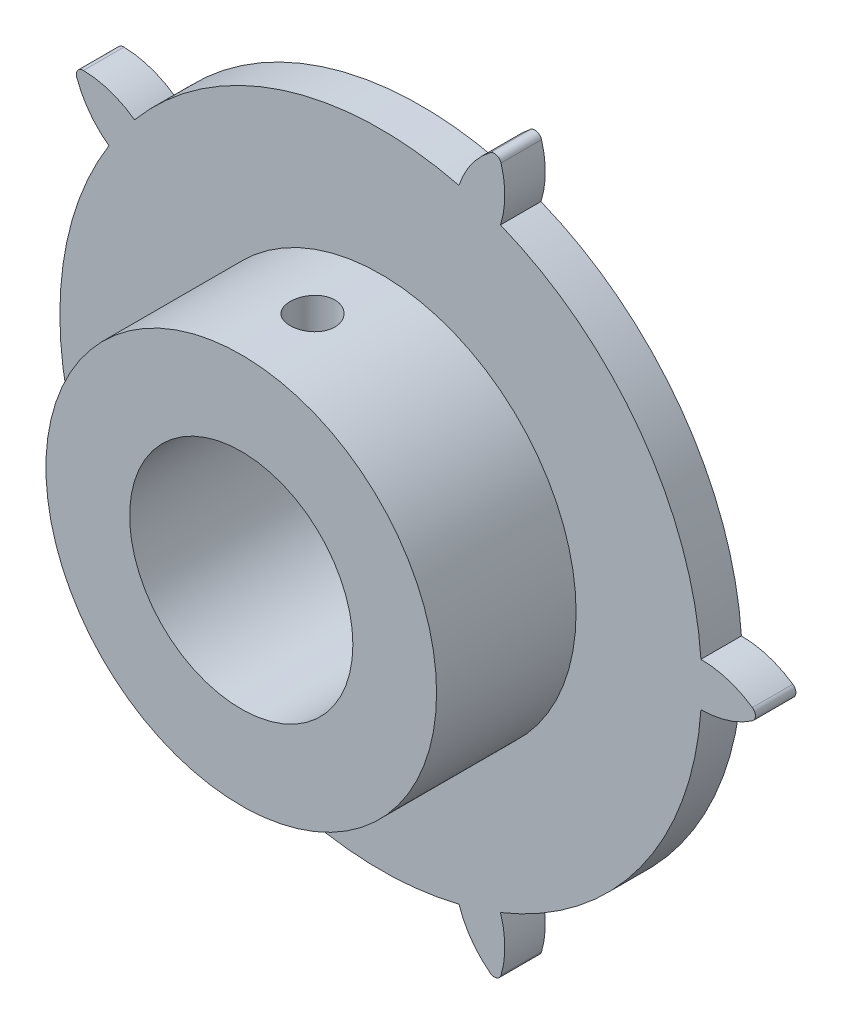
SolidWorks part; units mm, degrees
ref_plane "Front Plane" through (0, 0, 0) normal (0, 0, 1) x (1, 0, 0)
ref_plane "Top Plane" through (0, 0, 0) normal (0, 1, 0) x (1, 0, 0)
ref_plane "Right Plane" through (0, 0, 0) normal (1, 0, 0) x (0, 0, -1)
sketch "Sketch1" plane through (0, 0, 0) normal (0, 0, 1) x (1, 0, 0)
  circle A0 centre (0, 0) radius 11.5
extrude "Boss-Extrude1" add sketch "Sketch1" along normal blind 1.45
sketch "Sketch2" plane through (0, 0, 1.45) normal (0, 0, 1) x (1, 0, 0)
  line L3 (11.4664, -0.7818) -> (11.4664, 0.7818)
  arc A0 (11.4664, 0.7818) -> (13.3176, 0.2059) centre (11.4664, -2.4818) cw
  arc A1 (11.4664, -0.7818) -> (13.3176, -0.2059) centre (11.4664, 2.4818) ccw
  arc A2 (13.3176, 0.2059) -> (13.3176, -0.2059) centre (13.1758, 0) cw
  dimension "D1" = 0.25
extrude "Boss-Extrude2" add sketch "Sketch2" against normal blind 1.45
pattern_circular "CirPattern2" count 5 over 360 about axis through (0, 0, 0) along (0, 0, 1) of "Boss-Extrude2"
sketch "Sketch4" plane through (0, 0, 1.45) normal (0, 0, 1) x (1, 0, 0)
  circle A0 centre (0, 0) radius 4
extrude "Cut-Extrude1" cut sketch "Sketch4" against normal blind 1.45
sketch "Sketch5" plane through (0, 0, 1.45) normal (0, 0, 1) x (1, 0, 0)
  circle A0 centre (0, 0) radius 4
  circle A1 centre (0, 0) radius 7
extrude "Boss-Extrude3" add sketch "Sketch5" along normal blind 5
hole_wizard "M2x0.4 Tapped Hole3" positions "3DSketch6" profile "Sketch10" tap size "M2x0.4" standard "Ansi Metric"
sketch3d "3DSketch6"
  point P0 (-0.022, 7, 3.8749)
sketch "Sketch10" plane through (-0.022, 7, 3.8749) normal (0, 0, 1) x (-1, -0.0031, 0)
  line L0 (0, 0) -> (0, 5.6807)
  line L1 (0, 5.6807) -> (0.8, 5.2)
  line L2 (0.8, 5.2) -> (0.8, 0)
  line L5 (0.8, 0) -> (0, 0)
  line L10 (0, 5.6807) -> (-0.8, 5.2) construction
  line L11 (0, -6.35) -> (0, 107.95) construction
  dimension "Tap Drill Dia." = 1.6
  dimension "Tap Drill Depth" = 5.2
  dimension "Drill Angle" = 118
